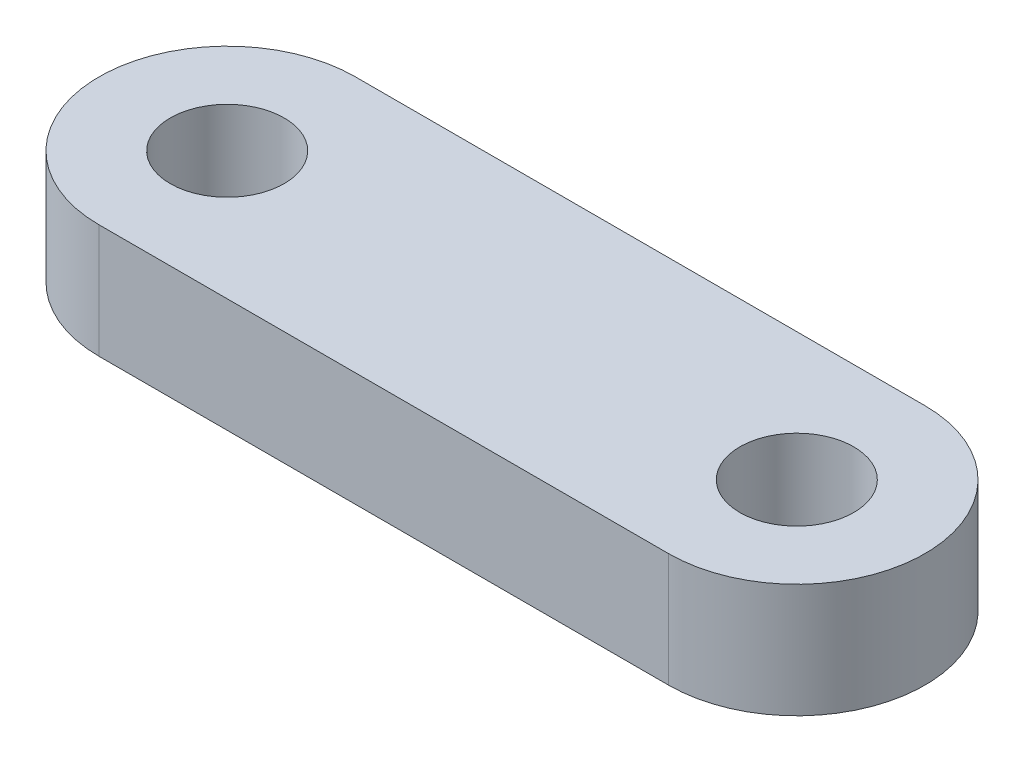
SolidWorks part; units mm, degrees
ref_plane "Спереди" through (0, 0, 0) normal (0, 0, 1) x (1, 0, 0)
ref_plane "Сверху" through (0, 0, 0) normal (0, 1, 0) x (1, 0, 0)
ref_plane "Справа" through (0, 0, 0) normal (1, 0, 0) x (0, 0, -1)
sketch "Эскиз1" plane through (0, 0, 0) normal (0, 1, 0) x (1, 0, 0)
  line L0 (0, 4.5) -> (20, 4.5)
  line L1 (0, -4.5) -> (20, -4.5)
  circle A0 centre (0, 0) radius 2
  circle A1 centre (20, 0) radius 2
  arc A2 (0, 4.5) -> (0, -4.5) centre (0, 0) ccw
  arc A3 (20, -4.5) -> (20, 4.5) centre (20, 0) ccw
  dimension "D1" = 20
extrude "Вытянуть1" add sketch "Эскиз1" along normal blind 4
